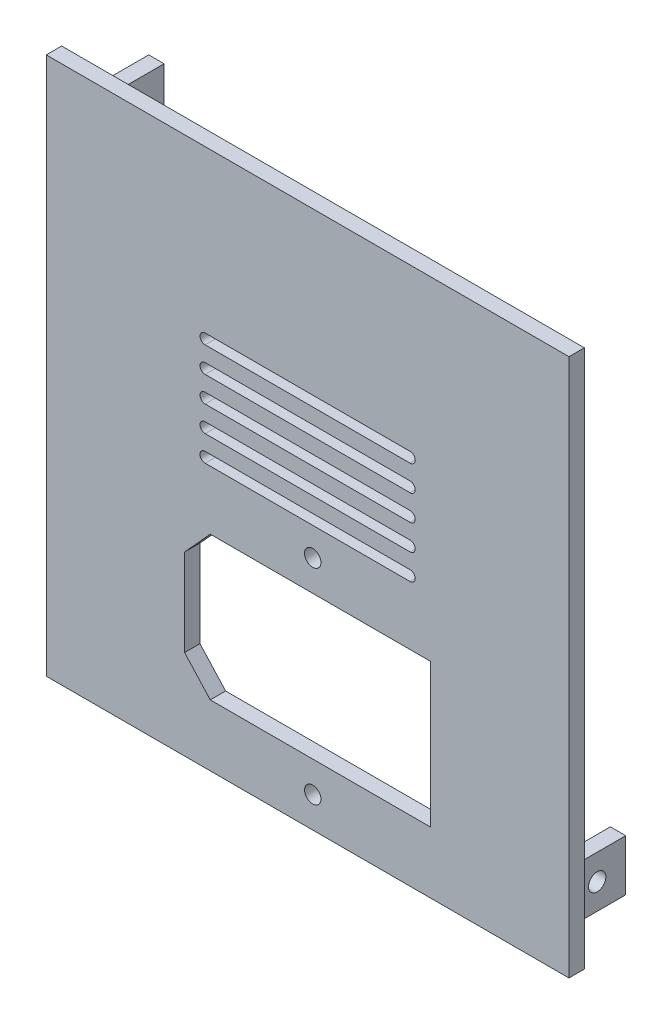
SolidWorks part; units mm, degrees
ref_plane "Front Plane" through (0, 0, 0) normal (0, 0, 1) x (1, 0, 0)
ref_plane "Top Plane" through (0, 0, 0) normal (0, 1, 0) x (1, 0, 0)
ref_plane "Right Plane" through (0, 0, 0) normal (1, 0, 0) x (0, 0, -1)
sketch "Sketch2" plane through (0, 0, 0) normal (0, 0, 1) x (1, 0, 0)
  line L1 (51, 52.5) -> (-51, 52.5)
  line L2 (51, 52.5) -> (51, -52.5)
  line L3 (51, -52.5) -> (-51, -52.5)
  line L4 (-51, 52.5) -> (-51, -52.5)
  line L5 (51, 52.5) -> (-51, -52.5) construction
  line L6 (51, -52.5) -> (-51, 52.5) construction
  point P0 (0, 0)
  dimension "D1" = 102
  dimension "D2" = 105
extrude "Boss-Extrude1" add sketch "Sketch2" along normal mid plane 3
sketch "Sketch3" plane through (0, 0, 1.5) normal (0, 0, 1) x (1, 0, 0)
  line L0 (-20, 0) -> (20, 0) construction
  line L1 (20, 25) -> (-20, 25) construction
  line L2 (20, 25) -> (20, -25) construction
  line L3 (20, -25) -> (-20, -25) construction
  line L4 (-20, 25) -> (-20, -25) construction
  line L5 (20, 25) -> (-20, -25) construction
  line L6 (20, -25) -> (-20, 25) construction
  line L7 (-20, 1) -> (20, 1)
  line L8 (-20, -1) -> (20, -1)
  line L9 (-20, 5) -> (20, 5) construction
  line L10 (-20, 6) -> (20, 6)
  line L11 (-20, 4) -> (20, 4)
  line L12 (-20, 10) -> (20, 10) construction
  line L13 (-20, 11) -> (20, 11)
  line L14 (-20, 9) -> (20, 9)
  line L15 (-20, 15) -> (20, 15) construction
  line L16 (-20, 16) -> (20, 16)
  line L17 (-20, 14) -> (20, 14)
  line L18 (-20, 20) -> (20, 20) construction
  line L19 (-20, 21) -> (20, 21)
  line L20 (-20, 19) -> (20, 19)
  arc A0 (-20, 1) -> (-20, -1) centre (-20, 0) ccw
  arc A1 (20, -1) -> (20, 1) centre (20, 0) ccw
  arc A2 (-20, 6) -> (-20, 4) centre (-20, 5) ccw
  arc A3 (20, 4) -> (20, 6) centre (20, 5) ccw
  arc A4 (-20, 11) -> (-20, 9) centre (-20, 10) ccw
  arc A5 (20, 9) -> (20, 11) centre (20, 10) ccw
  arc A6 (-20, 16) -> (-20, 14) centre (-20, 15) ccw
  arc A7 (20, 14) -> (20, 16) centre (20, 15) ccw
  arc A8 (-20, 21) -> (-20, 19) centre (-20, 20) ccw
  arc A9 (20, 19) -> (20, 21) centre (20, 20) ccw
  point P0 (0, 0)
  point P8 (0, 0)
  point P15 (0, 5)
  point P20 (0, 10)
  point P29 (0, 15)
  point P34 (0, 20)
  dimension "D1" = 40
  dimension "D2" = 50
  dimension "D3" = 2
  dimension "D4" = 5
  dimension "D5" = 10
  dimension "D6" = 2
  dimension "D7" = 2
  dimension "D8" = 15
  dimension "D9" = 20
  dimension "D10" = 2
  dimension "D11" = 2
extrude "Cut-Extrude1" cut sketch "Sketch3" against normal blind 10
sketch "Sketch4" plane through (0, 0, 1.5) normal (0, 0, 1) x (1, 0, 0)
  line L0 (-19, -12.5) -> (24, -12.5)
  line L1 (24, -12.5) -> (24, -40.5)
  line L2 (24, -40.5) -> (-19, -40.5)
  line L3 (-19, -40.5) -> (-24, -35)
  line L4 (-24, -35) -> (-24, -18)
  line L5 (-24, -18) -> (-19, -12.5)
  line L6 (0, -52.5) -> (0, -46.8699) construction
  line L7 (-51, -52.5) -> (51, -52.5) construction
  dimension "D1" = 17
  dimension "D2" = 48
  dimension "D3" = 43
  dimension "D4" = 28
  dimension "D5" = 12
extrude "Cut-Extrude2" cut sketch "Sketch4" against normal blind 10
sketch "Sketch5" plane through (0, 0, -1.5) normal (0, 0, -1) x (-1, 0, 0)
  line L0 (51, 52.5) -> (51, -52.5) construction
  line L1 (51, -42.5) -> (48, -42.5)
  line L2 (51, -42.5) -> (51, -32.5)
  line L3 (51, -32.5) -> (48, -32.5)
  line L4 (48, -42.5) -> (48, -32.5)
  line L5 (51, -52.5) -> (-51, -52.5) construction
  dimension "D1" = 3
  dimension "D2" = 20
  dimension "D3" = 10
extrude "Boss-Extrude2" add sketch "Sketch5" along normal blind 17
fillet "Fillet1" radius 3 3 edges at (-49.5, -42.5, -1.5) (-49.5, -32.5, -1.5) (-48, -37.5, -1.5)
hole_wizard "M3 Clearance Hole1" positions "Sketch6" profile "Sketch7" hole size "M3" standard "ISO" end condition up to next
sketch "Sketch6" plane through (-51, 0, 0) normal (-1, 0, 0) x (0, 0, 1)
  line L0 (-18.5, -37.5) -> (-17.5775, -37.5) construction
  line L1 (-18.5, -42.5) -> (-18.5, -32.5) construction
  line L3 (-1.5, 52.5) -> (-1.5, -29.5) construction
  point P0 (-13.5, -37.5)
  dimension "D1" = 12
sketch "Sketch7" plane through (-51, -37.5, -13.5) normal (0, 1, 0) x (0, 0, 1)
  line L0 (0, 0) -> (0, 3)
  line L1 (0, 3) -> (1.7, 3)
  line L2 (1.7, 3) -> (1.7, 0)
  line L5 (1.7, 0) -> (0, 0)
  line L11 (0, -6.35) -> (0, 107.95) construction
  dimension "Thru Hole Dia." = 3.4
  dimension "Thru Hole Depth" = 3
sketch "Sketch8" plane through (0, 0, -1.5) normal (0, 0, -1) x (-1, 0, 0)
  line L0 (51, -52.5) -> (-51, -52.5) construction
  line L1 (-44.08, -40.91) -> (-41.08, -40.91)
  line L2 (-44.08, -40.91) -> (-44.08, -50.91)
  line L3 (-44.08, -50.91) -> (-41.08, -50.91)
  line L4 (-41.08, -40.91) -> (-41.08, -50.91)
  line L5 (-44.08, -40.91) -> (-41.08, -50.91) construction
  line L6 (-44.08, -50.91) -> (-41.08, -40.91) construction
  line L7 (-51, -52.5) -> (-51, 52.5) construction
  point P0 (-42.58, -45.91)
  dimension "D1" = 6.59
  dimension "D2" = 10
  dimension "D3" = 3
  dimension "D4" = 6.92
extrude "Boss-Extrude3" add sketch "Sketch8" along normal blind 15
hole_wizard "M3 Clearance Hole2" positions "Sketch9" profile "Sketch10" hole size "M3" standard "ISO" end condition up to next
sketch "Sketch9" plane through (44.08, 0, 0) normal (1, 0, 0) x (0, 0, -1)
  line L0 (-1.5, -52.5) -> (-1.5, 52.5) construction
  line L1 (16.5, -45.91) -> (13.8622, -45.91) construction
  line L2 (16.5, -40.91) -> (16.5, -50.91) construction
  line L4 (16.5, -40.91) -> (1.5, -40.91) construction
  line L5 (16.5, -50.91) -> (1.5, -50.91) construction
  point P0 (10.93, -45.91)
  dimension "D1" = 12.43
sketch "Sketch10" plane through (44.08, -45.91, -10.93) normal (0, 1, 0) x (0, 0, -1)
  line L0 (0, 0) -> (0, 3)
  line L1 (0, 3) -> (1.7, 3)
  line L2 (1.7, 3) -> (1.7, 0)
  line L5 (1.7, 0) -> (0, 0)
  line L11 (0, -6.35) -> (0, 107.95) construction
  dimension "Thru Hole Dia." = 3.4
  dimension "Thru Hole Depth" = 3
fillet "Fillet2" radius 3 3 edges at (41.08, -45.91, -1.5) (42.58, -40.91, -1.5) (44.08, -45.91, -1.5)
fillet "Fillet3" radius 1 1 edges at (42.58, -50.91, -1.5)
mirror "Mirror1" about plane through (0, 0, 0) normal (0, 1, 0) of "Fillet1", "Boss-Extrude2", "M3 Clearance Hole1"
hole_wizard "M3 Clearance Hole3" positions "Sketch11" profile "Sketch12" hole size "M3" standard "ISO" end condition up to next
sketch "Sketch11" plane through (0, 0, -1.5) normal (0, 0, -1) x (-1, 0, 0)
  line L0 (-24, -12.5) -> (-24, -40.5) construction
  line L1 (-24, -26.5) -> (-18.743, -26.5) construction
  point P0 (-1, -6.5)
  point P2 (-1, -46.5)
  dimension "D1" = 40
  dimension "D2" = 23
sketch "Sketch12" plane through (1, -6.5, -1.5) normal (1, 0, 0) x (0, 1, 0)
  line L0 (0, 0) -> (0, 3)
  line L1 (0, 3) -> (1.6, 3)
  line L2 (1.6, 3) -> (1.6, 0)
  line L5 (1.6, 0) -> (0, 0)
  line L11 (0, -6.35) -> (0, 107.95) construction
  dimension "Thru Hole Dia." = 3.2
  dimension "Thru Hole Depth" = 3
